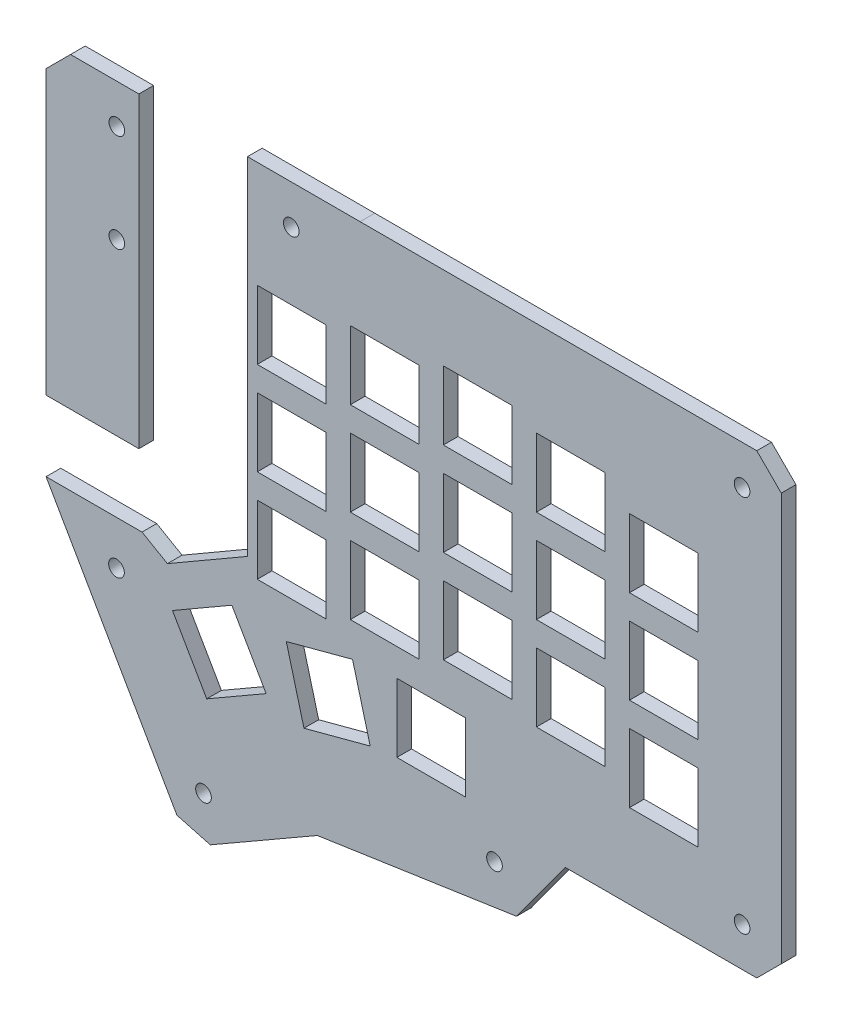
SolidWorks part; units mm, degrees
ref_plane "Plan de face" through (0, 0, 0) normal (0, 0, 1) x (1, 0, 0)
ref_plane "Plan de dessus" through (0, 0, 0) normal (0, 1, 0) x (1, 0, 0)
ref_plane "Plan de droite" through (0, 0, 0) normal (1, 0, 0) x (0, 0, -1)
sketch "Switchplate" plane through (0, 0, 0) normal (0, 0, 1) x (1, 0, 0)
  line L0 (-117.3419, -15.4198) -> (-103.3409, -15.4198)
  line L1 (-103.3409, -15.4198) -> (-103.3409, -29.4208)
  line L2 (-103.3409, -29.4208) -> (-117.3419, -29.4208)
  line L3 (-117.3419, -29.4208) -> (-117.3419, -15.4198)
  line L4 (-98.3406, -27.0457) -> (-98.3406, -13.0447)
  line L5 (-98.3406, -13.0447) -> (-84.3396, -13.0447)
  line L6 (-84.3396, -13.0447) -> (-84.3396, -27.0457)
  line L7 (-84.3396, -27.0457) -> (-98.3406, -27.0457)
  line L8 (-79.3392, -24.6705) -> (-79.3392, -10.6695)
  line L9 (-79.3392, -10.6695) -> (-65.3382, -10.6695)
  line L10 (-65.3382, -10.6695) -> (-65.3382, -24.6705)
  line L11 (-65.3382, -24.6705) -> (-79.3392, -24.6705)
  line L12 (-60.3379, -27.0457) -> (-60.3379, -13.0447)
  line L13 (-60.3379, -13.0447) -> (-46.3369, -13.0447)
  line L14 (-46.3369, -13.0447) -> (-46.3369, -27.0457)
  line L15 (-46.3369, -27.0457) -> (-60.3379, -27.0457)
  line L16 (-41.3365, -31.796) -> (-41.3365, -17.795)
  line L17 (-41.3365, -17.795) -> (-27.3355, -17.795)
  line L18 (-27.3355, -17.795) -> (-27.3355, -31.796)
  line L19 (-27.3355, -31.796) -> (-41.3365, -31.796)
  line L24 (-117.3419, -34.4212) -> (-103.3409, -34.4212)
  line L25 (-103.3409, -34.4212) -> (-103.3409, -48.4222)
  line L26 (-103.3409, -48.4222) -> (-117.3419, -48.4222)
  line L27 (-117.3419, -48.4222) -> (-117.3419, -34.4212)
  line L28 (-98.3406, -32.046) -> (-84.3396, -32.046)
  line L29 (-84.3396, -32.046) -> (-84.3396, -46.047)
  line L30 (-84.3396, -46.047) -> (-98.3406, -46.047)
  line L31 (-98.3406, -46.047) -> (-98.3406, -32.046)
  line L32 (-79.3392, -29.6709) -> (-65.3382, -29.6709)
  line L33 (-65.3382, -29.6709) -> (-65.3382, -43.6718)
  line L34 (-65.3382, -43.6718) -> (-79.3392, -43.6718)
  line L35 (-79.3392, -43.6718) -> (-79.3392, -29.6709)
  line L36 (-60.3379, -32.046) -> (-46.3369, -32.046)
  line L37 (-46.3369, -32.046) -> (-46.3369, -46.047)
  line L38 (-46.3369, -46.047) -> (-60.3379, -46.047)
  line L39 (-60.3379, -46.047) -> (-60.3379, -32.046)
  line L40 (-41.3365, -36.7964) -> (-27.3355, -36.7964)
  line L41 (-27.3355, -36.7964) -> (-27.3355, -50.7973)
  line L42 (-27.3355, -50.7973) -> (-41.3365, -50.7973)
  line L43 (-41.3365, -50.7973) -> (-41.3365, -36.7964)
  line L52 (-41.3365, -55.7977) -> (-27.3355, -55.7977)
  line L53 (-27.3355, -55.7977) -> (-27.3355, -69.7987)
  line L54 (-27.3355, -69.7987) -> (-41.3365, -69.7987)
  line L55 (-41.3365, -69.7987) -> (-41.3365, -55.7977)
  line L56 (-60.3379, -51.0474) -> (-46.3369, -51.0474)
  line L57 (-46.3369, -51.0474) -> (-46.3369, -65.0484)
  line L58 (-46.3369, -65.0484) -> (-60.3379, -65.0484)
  line L59 (-60.3379, -65.0484) -> (-60.3379, -51.0474)
  line L60 (-79.3392, -48.6722) -> (-65.3382, -48.6722)
  line L61 (-65.3382, -48.6722) -> (-65.3382, -62.6732)
  line L62 (-65.3382, -62.6732) -> (-79.3392, -62.6732)
  line L63 (-79.3392, -62.6732) -> (-79.3392, -48.6722)
  line L64 (-98.3406, -51.0474) -> (-84.3396, -51.0474)
  line L65 (-84.3396, -51.0474) -> (-84.3396, -65.0484)
  line L66 (-84.3396, -65.0484) -> (-98.3406, -65.0484)
  line L67 (-98.3406, -65.0484) -> (-98.3406, -51.0474)
  line L68 (-117.3419, -53.4225) -> (-103.3409, -53.4225)
  line L69 (-103.3409, -53.4225) -> (-103.3409, -67.4235)
  line L70 (-103.3409, -67.4235) -> (-117.3419, -67.4235)
  line L71 (-117.3419, -67.4235) -> (-117.3419, -53.4225)
  line L72 (-88.8399, -70.6738) -> (-74.8389, -70.6738)
  line L73 (-74.8389, -70.6738) -> (-74.8389, -84.6747)
  line L74 (-74.8389, -84.6747) -> (-88.8399, -84.6747)
  line L75 (-88.8399, -84.6747) -> (-88.8399, -70.6738)
  line L76 (-111.4175, -75.4665) -> (-97.8899, -71.8565)
  line L77 (-97.8899, -71.8565) -> (-94.28, -85.3841)
  line L78 (-94.28, -85.3841) -> (-107.8075, -88.9941)
  line L79 (-107.8075, -88.9941) -> (-111.4175, -75.4665)
  line L80 (-134.6581, -81.5997) -> (-122.5281, -74.6075)
  line L81 (-122.5281, -74.6075) -> (-115.5359, -86.7375)
  line L82 (-115.5359, -86.7375) -> (-127.6659, -93.7297)
  line L83 (-127.6659, -93.7297) -> (-134.6581, -81.5997)
  line L86 (-6.3391, -71.9336) -> (-62.0853, -71.9336) construction
  line L89 (-72.824, -86.6446) -> (-62.0853, -71.9336) construction
  line L96 (-109.7697, -91.4639) -> (-73.0906, -86.6918) construction
  line L97 (-124.664, -99.8297) -> (-110.3971, -91.5881) construction
  line L98 (-139.9408, -76.5013) -> (-126.7151, -99.4281) construction
  line L99 (-119.8527, -15.5421) -> (-139.6028, -15.5421) construction
  line L100 (-100.8528, -13.2921) -> (-118.8527, -13.2921) construction
  line L101 (-63.8455, -8.5421) -> (-80.8528, -8.5421) construction
  line L102 (-44.8455, -10.792) -> (-62.8485, -10.792) construction
  line L103 (-25.8456, -15.5421) -> (-43.8486, -15.5421) construction
  line L104 (-6.8456, -15.5421) -> (-23.8529, -15.5421) construction
  line L105 (-6.2741, -71.3672) -> (-6.2741, -16.1136) construction
  line L106 (-23.8529, -71.9423) -> (-6.8456, -71.9423) construction
  line L107 (-61.8455, -71.9423) -> (-25.8456, -71.9423) construction
  line L108 (-72.6738, -86.4911) -> (-62.1363, -72.0583) construction
  line L109 (-140.1743, -16.1136) -> (-140.1743, -75.5958) construction
  line L110 (-134.3462, 1.5705) -> (-134.3466, -55.7217) construction
  line L111 (-134.3466, -55.7217) -> (-160.479, -70.8411) construction
  line L112 (-160.479, -70.8411) -> (-133.7613, -117.344)
  line L113 (-126.937, -119.1852) -> (-105.0783, -106.604)
  line L114 (-105.0783, -106.604) -> (-64.4097, -100.5586)
  line L115 (-64.4097, -100.5586) -> (-54.4636, -86.9336)
  line L116 (-15.3391, -86.9336) -> (-54.4636, -86.9336)
  line L117 (-10.3391, -81.9336) -> (-10.3391, 1.3161)
  line L122 (-15.3391, 6.3163) -> (-96.3444, 6.3209)
  line L129 (8.6609, -86.9336) -> (8.6609, -0.6796) construction
  line L130 (-48.3431, 6.3182) -> (-96.3444, 6.3209) construction
  line L131 (-115.3458, 1.5705) -> (-134.3462, 1.5705) construction
  line L132 (-160.479, -3.4295) -> (-160.479, -70.8411)
  line L134 (-119.3463, 1.5705) -> (-119.3466, -64.3728)
  line L135 (-119.3466, -64.3728) -> (-135.695, -73.8315)
  line L136 (-140.0228, -71.3355) -> (-140.0228, 1.5705) construction
  line L138 (-160.479, -70.8411) -> (-131.2704, -121.6794) construction
  line L139 (-131.2704, -121.6794) -> (-105.0783, -106.604) construction
  line L140 (-133.7613, -117.344) -> (-126.937, -119.1852)
  line L142 (-10.3391, 1.3161) -> (-15.3391, 6.3163)
  line L143 (8.6609, -86.9336) -> (-54.4636, -86.9336) construction
  line L147 (-103.3409, 6.3209) -> (-96.3444, 6.3209)
  line L148 (-103.3409, 6.3209) -> (-119.3463, 6.3209)
  line L149 (-119.3463, 6.3209) -> (-119.3463, 1.5705)
  line L150 (-140.0228, 1.5705) -> (-140.0228, 6.3209) construction
  line L151 (-141.5228, 6.3209) -> (-155.479, 6.3209)
  line L152 (-160.479, 1.3209) -> (-160.479, -3.4295)
  line L153 (-155.479, 6.3209) -> (-160.479, 1.3209)
  line L154 (8.6609, -1.685) -> (-119.3463, -1.6779) construction
  line L155 (-146.0924, -79.8227) -> (-128.3223, -110.752) construction
  line L156 (-128.3223, -110.752) -> (-107.7547, -98.9139) construction
  line L157 (-140.8899, -76.8336) -> (-126.1111, -102.5565) construction
  line L158 (-126.1111, -102.5565) -> (-109.762, -93.1464) construction
  line L159 (-109.762, -93.1464) -> (-72.2631, -87.5722) construction
  line L160 (-72.2631, -87.5722) -> (-61.5772, -72.9336) construction
  line L161 (-5.3391, -72.9336) -> (-61.5772, -72.9336) construction
  line L162 (-5.3391, -72.9336) -> (-5.3391, -14.6796) construction
  line L163 (-5.3391, -14.6796) -> (-43.3418, -14.6796) construction
  line L164 (-43.3418, -14.6796) -> (-43.3418, -9.9293) construction
  line L165 (-43.3418, -9.9293) -> (-62.3431, -9.9293) construction
  line L166 (-62.3431, -9.9293) -> (-62.3431, -7.681) construction
  line L167 (-62.3431, -7.681) -> (-82.3444, -7.6799) construction
  line L168 (-82.3444, -7.6799) -> (-82.3444, -9.9293) construction
  line L169 (-82.3444, -9.9293) -> (-101.3458, -9.9293) construction
  line L170 (-101.3458, -9.9293) -> (-101.3458, -12.4295) construction
  line L171 (-101.3458, -12.4295) -> (-120.3463, -12.4295) construction
  line L172 (-120.3463, -12.4295) -> (-120.3466, -64.3728) construction
  line L173 (-119.8474, -63.5072) -> (-140.5236, -75.4699) construction
  line L174 (-107.7547, -98.9139) -> (-68.8973, -93.1378) construction
  line L175 (-68.8973, -93.1378) -> (-58.5285, -78.9336) construction
  line L176 (0.6609, -78.9336) -> (-58.5285, -78.9336) construction
  line L177 (-18.3391, -78.9336) -> (-18.3391, -1.6845) construction
  line L178 (-62.3428, -1.681) -> (-82.3441, -1.6799) construction
  line L179 (0.6609, -78.9336) -> (0.6609, -14.6796) construction
  line L180 (-146.0228, -76.3355) -> (-146.0228, 1.5705) construction
  line L181 (-140.0228, -76.3355) -> (-140.0228, 1.5705) construction
  line L182 (-135.695, -73.8315) -> (-141.5228, -70.4704)
  line L185 (-10.3391, -81.9336) -> (-15.3391, -86.9336)
  line L186 (-146.0228, -1.6779) -> (-146.0228, -19.3841) construction
  line L187 (-146.0228, -1.6779) -> (-146.0228, -21.6824) construction
  line L188 (-141.5228, -70.4704) -> (-141.5228, 1.5705)
  line L189 (-141.5228, 1.5705) -> (-141.5228, 6.3209)
  line L191 (-141.5228, -71.3355) -> (-141.5228, 1.5705) construction
  line L217 (-6.3391, -71.9336) -> (-6.3391, -15.6796) construction
  line L220 (-6.3391, -15.6796) -> (-44.3418, -15.6796) construction
  line L221 (-44.3418, -15.6796) -> (-44.3418, -10.9293) construction
  line L222 (-44.3418, -10.9293) -> (-63.3431, -10.9293) construction
  line L223 (-63.3431, -10.9293) -> (-63.3431, -8.681) construction
  line L224 (-63.3431, -8.681) -> (-81.3444, -8.68) construction
  line L225 (-81.3444, -8.68) -> (-81.3444, -10.9293) construction
  line L226 (-81.3444, -10.9293) -> (-100.3458, -10.9293) construction
  line L227 (-100.3458, -10.9293) -> (-100.3458, -13.4295) construction
  line L228 (-100.3458, -13.4295) -> (-119.3463, -13.4295) construction
  line L231 (-119.3463, -13.4295) -> (-119.3466, -64.3728) construction
  line L232 (-119.3466, -64.3728) -> (-140.0228, -76.3355) construction
  line L233 (-140.0228, -76.3355) -> (-125.7426, -101.1906) construction
  line L234 (-125.7426, -101.1906) -> (-110.0965, -92.1851) construction
  line L235 (-110.0965, -92.1851) -> (-72.824, -86.6446) construction
  line L328 (-48.3431, 4.0707) -> (-48.3431, 6.3182) construction
  line L329 (-29.3418, 4.0707) -> (-48.3431, 4.0707) construction
  line L330 (-29.3418, -0.6796) -> (-29.3418, 4.0707) construction
  line L331 (8.6609, -0.6796) -> (-29.3418, -0.6796) construction
  line L332 (-115.3458, 4.0707) -> (-115.3458, 1.5705) construction
  line L333 (-96.3444, 4.0707) -> (-115.3458, 4.0707) construction
  line L334 (-96.3444, 6.3209) -> (-96.3444, 4.0707) construction
  circle A2 centre (-18.3391, -1.6845) radius 1.6
  circle A3 centre (-18.3391, -1.6845) radius 3 construction
  circle A4 centre (-110.3971, -1.6784) radius 1.6
  circle A5 centre (-18.3391, -78.9336) radius 1.6
  circle A6 centre (-68.8973, -93.1378) radius 1.6
  circle A7 centre (-128.3223, -110.752) radius 1.6
  circle A8 centre (-146.0924, -79.8227) radius 1.6
  circle A9 centre (-146.0228, -1.6779) radius 1.6
  circle A10 centre (-146.0228, -21.6824) radius 1.6
  point P138 (-160.479, 1.5705)
  point P139 (-10.3391, 6.3161)
  point P150 (-160.479, 6.3209)
  point P200 (-10.3391, -86.9336)
  dimension "D3" = 3.2
  dimension "D4" = 6
  dimension "D6" = 3.2
  dimension "D7" = 3.2
  dimension "D8" = 3.2
  dimension "D9" = 3.2
  dimension "D10" = 3.2
  dimension "D15" = 3.2
  dimension "D16" = 3.2
  dimension "D2" = 6
  dimension "D1" = 15
  dimension "D5" = 1
  dimension "D13" = 6
  dimension "D17" = 1.5
extrude "Boss.-Extru.2" add sketch "Switchplate" along normal blind 3
sketch "Esquisse1" plane through (0, 0, 3) normal (0, 0, 1) x (1, 0, 0)
  line L0 (-160.479, -70.8411) -> (-140.0228, -70.8411)
  line L1 (-140.0228, -71.3355) -> (-140.0228, 1.5705) construction
  line L2 (-117.3419, -53.4225) -> (-140.0228, -53.4225) construction
  line L3 (-140.0228, -53.4225) -> (-140.0228, -56.4207) construction
  line L4 (-140.0228, -56.4207) -> (-140.0228, -70.8411)
  line L5 (-140.0228, -56.4207) -> (-160.479, -56.4207)
  line L6 (-160.479, -3.4295) -> (-160.479, -70.8411) construction
  line L7 (-160.479, -56.4207) -> (-160.479, -70.8411)
extrude "Enlèv. mat.-Extru.1" cut sketch "Esquisse1" against normal blind 10
sketch "Esquisse2" plane through (0, 0, 3) normal (0, 0, 1) x (1, 0, 0)
  line L0 (-81.3444, -8.68) -> (-81.3444, -10.9293) construction
  line L1 (-63.3431, -8.681) -> (-81.3444, -8.68) construction
  line L2 (-63.3431, -10.9293) -> (-63.3431, -8.681) construction
  line L3 (-44.3418, -10.9293) -> (-63.3431, -10.9293) construction
  line L4 (-44.3418, -15.6796) -> (-44.3418, -10.9293) construction
  line L5 (-6.3391, -15.6796) -> (-44.3418, -15.6796) construction
  line L6 (-6.3391, -71.9336) -> (-6.3391, -15.6796) construction
  line L7 (-6.3391, -71.9336) -> (-62.0853, -71.9336) construction
  line L8 (-72.824, -86.6446) -> (-62.0853, -71.9336) construction
  line L9 (-110.0965, -92.1851) -> (-72.824, -86.6446) construction
  line L10 (-125.7426, -101.1906) -> (-110.0965, -92.1851) construction
  line L11 (-140.0228, -76.3355) -> (-125.7426, -101.1906) construction
  line L12 (-119.3466, -64.3728) -> (-140.0228, -76.3355) construction
  line L13 (-119.3463, -13.4295) -> (-119.3466, -64.3728) construction
  line L14 (-100.3458, -13.4295) -> (-119.3463, -13.4295) construction
  line L15 (-100.3458, -10.9293) -> (-100.3458, -13.4295) construction
  line L16 (-81.3444, -10.9293) -> (-100.3458, -10.9293) construction
  line L17 (-81.3444, -8.68) -> (-81.3444, -10.9293)
  line L18 (-63.3431, -8.681) -> (-81.3444, -8.68)
  line L19 (-63.3431, -10.9293) -> (-63.3431, -8.681)
  line L20 (-44.3418, -10.9293) -> (-63.3431, -10.9293)
  line L21 (-44.3418, -15.6796) -> (-44.3418, -10.9293)
  line L22 (-6.3391, -15.6796) -> (-44.3418, -15.6796)
  line L23 (-6.3391, -71.9336) -> (-6.3391, -15.6796)
  line L24 (-6.3391, -71.9336) -> (-62.0853, -71.9336)
  line L25 (-72.824, -86.6446) -> (-62.0853, -71.9336)
  line L26 (-110.0965, -92.1851) -> (-72.824, -86.6446)
  line L27 (-125.7426, -101.1906) -> (-110.0965, -92.1851)
  line L28 (-140.0228, -76.3355) -> (-125.7426, -101.1906)
  line L29 (-119.3466, -64.3728) -> (-140.0228, -76.3355)
  line L30 (-119.3463, -13.4295) -> (-119.3466, -64.3728)
  line L31 (-100.3458, -13.4295) -> (-119.3463, -13.4295)
  line L32 (-100.3458, -10.9293) -> (-100.3458, -13.4295)
  line L33 (-81.3444, -10.9293) -> (-100.3458, -10.9293)
  line L34 (-127.6659, -93.7297) -> (-134.6581, -81.5997) construction
  line L35 (-115.5359, -86.7375) -> (-127.6659, -93.7297) construction
  line L36 (-122.5281, -74.6075) -> (-115.5359, -86.7375) construction
  line L37 (-134.6581, -81.5997) -> (-122.5281, -74.6075) construction
  line L38 (-107.8075, -88.9941) -> (-111.4175, -75.4665) construction
  line L39 (-94.28, -85.3841) -> (-107.8075, -88.9941) construction
  line L40 (-97.8899, -71.8565) -> (-94.28, -85.3841) construction
  line L41 (-111.4175, -75.4665) -> (-97.8899, -71.8565) construction
  line L42 (-88.8399, -84.6747) -> (-88.8399, -70.6738) construction
  line L43 (-74.8389, -84.6747) -> (-88.8399, -84.6747) construction
  line L44 (-74.8389, -70.6738) -> (-74.8389, -84.6747) construction
  line L45 (-88.8399, -70.6738) -> (-74.8389, -70.6738) construction
  line L46 (-98.3406, -65.0484) -> (-98.3406, -51.0474) construction
  line L47 (-84.3396, -65.0484) -> (-98.3406, -65.0484) construction
  line L48 (-84.3396, -51.0474) -> (-84.3396, -65.0484) construction
  line L49 (-98.3406, -51.0474) -> (-84.3396, -51.0474) construction
  line L50 (-117.3419, -67.4235) -> (-117.3419, -53.4225) construction
  line L51 (-103.3409, -67.4235) -> (-117.3419, -67.4235) construction
  line L52 (-103.3409, -53.4225) -> (-103.3409, -67.4235) construction
  line L53 (-117.3419, -53.4225) -> (-103.3409, -53.4225) construction
  line L54 (-117.3419, -48.4222) -> (-117.3419, -34.4212) construction
  line L55 (-103.3409, -48.4222) -> (-117.3419, -48.4222) construction
  line L56 (-103.3409, -34.4212) -> (-103.3409, -48.4222) construction
  line L57 (-117.3419, -34.4212) -> (-103.3409, -34.4212) construction
  line L58 (-98.3406, -46.047) -> (-98.3406, -32.046) construction
  line L59 (-84.3396, -46.047) -> (-98.3406, -46.047) construction
  line L60 (-84.3396, -32.046) -> (-84.3396, -46.047) construction
  line L61 (-98.3406, -32.046) -> (-84.3396, -32.046) construction
  line L62 (-79.3392, -43.6718) -> (-79.3392, -29.6709) construction
  line L63 (-65.3382, -43.6718) -> (-79.3392, -43.6718) construction
  line L64 (-65.3382, -29.6709) -> (-65.3382, -43.6718) construction
  line L65 (-79.3392, -29.6709) -> (-65.3382, -29.6709) construction
  line L66 (-60.3379, -46.047) -> (-60.3379, -32.046) construction
  line L67 (-46.3369, -46.047) -> (-60.3379, -46.047) construction
  line L68 (-46.3369, -32.046) -> (-46.3369, -46.047) construction
  line L69 (-60.3379, -32.046) -> (-46.3369, -32.046) construction
  line L70 (-79.3392, -62.6732) -> (-79.3392, -48.6722) construction
  line L71 (-65.3382, -62.6732) -> (-79.3392, -62.6732) construction
  line L72 (-65.3382, -48.6722) -> (-65.3382, -62.6732) construction
  line L73 (-79.3392, -48.6722) -> (-65.3382, -48.6722) construction
  line L74 (-60.3379, -65.0484) -> (-60.3379, -51.0474) construction
  line L75 (-46.3369, -65.0484) -> (-60.3379, -65.0484) construction
  line L76 (-46.3369, -51.0474) -> (-46.3369, -65.0484) construction
  line L77 (-60.3379, -51.0474) -> (-46.3369, -51.0474) construction
  line L78 (-41.3365, -69.7987) -> (-41.3365, -55.7977) construction
  line L79 (-27.3355, -69.7987) -> (-41.3365, -69.7987) construction
  line L80 (-27.3355, -55.7977) -> (-27.3355, -69.7987) construction
  line L81 (-41.3365, -55.7977) -> (-27.3355, -55.7977) construction
  line L82 (-22.3347, -69.7987) -> (-22.3347, -55.7977) construction
  line L83 (-8.3337, -69.7987) -> (-22.3347, -69.7987) construction
  line L84 (-8.3337, -55.7977) -> (-8.3337, -69.7987) construction
  line L85 (-22.3347, -55.7977) -> (-8.3337, -55.7977) construction
  line L86 (-41.3365, -50.7973) -> (-41.3365, -36.7964) construction
  line L87 (-27.3355, -50.7973) -> (-41.3365, -50.7973) construction
  line L88 (-27.3355, -36.7964) -> (-27.3355, -50.7973) construction
  line L89 (-41.3365, -36.7964) -> (-27.3355, -36.7964) construction
  line L90 (-22.3347, -50.7973) -> (-22.3347, -36.7964) construction
  line L91 (-8.3337, -50.7973) -> (-22.3347, -50.7973) construction
  line L92 (-8.3337, -36.7964) -> (-8.3337, -50.7973) construction
  line L93 (-22.3347, -36.7964) -> (-8.3337, -36.7964) construction
  line L94 (-22.3347, -31.796) -> (-22.3347, -17.795) construction
  line L95 (-8.3337, -31.796) -> (-22.3347, -31.796) construction
  line L96 (-8.3337, -17.795) -> (-8.3337, -31.796) construction
  line L97 (-22.3347, -17.795) -> (-8.3337, -17.795) construction
  line L98 (-41.3365, -31.796) -> (-41.3365, -17.795) construction
  line L99 (-27.3355, -31.796) -> (-41.3365, -31.796) construction
  line L100 (-27.3355, -17.795) -> (-27.3355, -31.796) construction
  line L101 (-41.3365, -17.795) -> (-27.3355, -17.795) construction
  line L102 (-60.3379, -27.0457) -> (-60.3379, -13.0447) construction
  line L103 (-46.3369, -27.0457) -> (-60.3379, -27.0457) construction
  line L104 (-46.3369, -13.0447) -> (-46.3369, -27.0457) construction
  line L105 (-60.3379, -13.0447) -> (-46.3369, -13.0447) construction
  line L106 (-79.3392, -24.6705) -> (-79.3392, -10.6695) construction
  line L107 (-65.3382, -24.6705) -> (-79.3392, -24.6705) construction
  line L108 (-65.3382, -10.6695) -> (-65.3382, -24.6705) construction
  line L109 (-79.3392, -10.6695) -> (-65.3382, -10.6695) construction
  line L110 (-98.3406, -27.0457) -> (-98.3406, -13.0447) construction
  line L111 (-84.3396, -27.0457) -> (-98.3406, -27.0457) construction
  line L112 (-84.3396, -13.0447) -> (-84.3396, -27.0457) construction
  line L113 (-98.3406, -13.0447) -> (-84.3396, -13.0447) construction
  line L114 (-117.3419, -29.4208) -> (-117.3419, -15.4198) construction
  line L115 (-103.3409, -29.4208) -> (-117.3419, -29.4208) construction
  line L116 (-103.3409, -15.4198) -> (-103.3409, -29.4208) construction
  line L117 (-117.3419, -15.4198) -> (-103.3409, -15.4198) construction
  line L118 (-127.6659, -93.7297) -> (-134.6581, -81.5997)
  line L119 (-115.5359, -86.7375) -> (-127.6659, -93.7297)
  line L120 (-122.5281, -74.6075) -> (-115.5359, -86.7375)
  line L121 (-134.6581, -81.5997) -> (-122.5281, -74.6075)
  line L122 (-107.8075, -88.9941) -> (-111.4175, -75.4665)
  line L123 (-94.28, -85.3841) -> (-107.8075, -88.9941)
  line L124 (-97.8899, -71.8565) -> (-94.28, -85.3841)
  line L125 (-111.4175, -75.4665) -> (-97.8899, -71.8565)
  line L126 (-88.8399, -84.6747) -> (-88.8399, -70.6738)
  line L127 (-74.8389, -84.6747) -> (-88.8399, -84.6747)
  line L128 (-74.8389, -70.6738) -> (-74.8389, -84.6747)
  line L129 (-88.8399, -70.6738) -> (-74.8389, -70.6738)
  line L130 (-98.3406, -65.0484) -> (-98.3406, -51.0474)
  line L131 (-84.3396, -65.0484) -> (-98.3406, -65.0484)
  line L132 (-84.3396, -51.0474) -> (-84.3396, -65.0484)
  line L133 (-98.3406, -51.0474) -> (-84.3396, -51.0474)
  line L134 (-117.3419, -67.4235) -> (-117.3419, -53.4225)
  line L135 (-103.3409, -67.4235) -> (-117.3419, -67.4235)
  line L136 (-103.3409, -53.4225) -> (-103.3409, -67.4235)
  line L137 (-117.3419, -53.4225) -> (-103.3409, -53.4225)
  line L138 (-117.3419, -48.4222) -> (-117.3419, -34.4212)
  line L139 (-103.3409, -48.4222) -> (-117.3419, -48.4222)
  line L140 (-103.3409, -34.4212) -> (-103.3409, -48.4222)
  line L141 (-117.3419, -34.4212) -> (-103.3409, -34.4212)
  line L142 (-98.3406, -46.047) -> (-98.3406, -32.046)
  line L143 (-84.3396, -46.047) -> (-98.3406, -46.047)
  line L144 (-84.3396, -32.046) -> (-84.3396, -46.047)
  line L145 (-98.3406, -32.046) -> (-84.3396, -32.046)
  line L146 (-79.3392, -43.6718) -> (-79.3392, -29.6709)
  line L147 (-65.3382, -43.6718) -> (-79.3392, -43.6718)
  line L148 (-65.3382, -29.6709) -> (-65.3382, -43.6718)
  line L149 (-79.3392, -29.6709) -> (-65.3382, -29.6709)
  line L150 (-60.3379, -46.047) -> (-60.3379, -32.046)
  line L151 (-46.3369, -46.047) -> (-60.3379, -46.047)
  line L152 (-46.3369, -32.046) -> (-46.3369, -46.047)
  line L153 (-60.3379, -32.046) -> (-46.3369, -32.046)
  line L154 (-79.3392, -62.6732) -> (-79.3392, -48.6722)
  line L155 (-65.3382, -62.6732) -> (-79.3392, -62.6732)
  line L156 (-65.3382, -48.6722) -> (-65.3382, -62.6732)
  line L157 (-79.3392, -48.6722) -> (-65.3382, -48.6722)
  line L158 (-60.3379, -65.0484) -> (-60.3379, -51.0474)
  line L159 (-46.3369, -65.0484) -> (-60.3379, -65.0484)
  line L160 (-46.3369, -51.0474) -> (-46.3369, -65.0484)
  line L161 (-60.3379, -51.0474) -> (-46.3369, -51.0474)
  line L162 (-41.3365, -69.7987) -> (-41.3365, -55.7977)
  line L163 (-27.3355, -69.7987) -> (-41.3365, -69.7987)
  line L164 (-27.3355, -55.7977) -> (-27.3355, -69.7987)
  line L165 (-41.3365, -55.7977) -> (-27.3355, -55.7977)
  line L166 (-22.3347, -69.7987) -> (-22.3347, -55.7977)
  line L167 (-8.3337, -69.7987) -> (-22.3347, -69.7987)
  line L168 (-8.3337, -55.7977) -> (-8.3337, -69.7987)
  line L169 (-22.3347, -55.7977) -> (-8.3337, -55.7977)
  line L170 (-41.3365, -50.7973) -> (-41.3365, -36.7964)
  line L171 (-27.3355, -50.7973) -> (-41.3365, -50.7973)
  line L172 (-27.3355, -36.7964) -> (-27.3355, -50.7973)
  line L173 (-41.3365, -36.7964) -> (-27.3355, -36.7964)
  line L174 (-22.3347, -50.7973) -> (-22.3347, -36.7964)
  line L175 (-8.3337, -50.7973) -> (-22.3347, -50.7973)
  line L176 (-8.3337, -36.7964) -> (-8.3337, -50.7973)
  line L177 (-22.3347, -36.7964) -> (-8.3337, -36.7964)
  line L178 (-22.3347, -31.796) -> (-22.3347, -17.795)
  line L179 (-8.3337, -31.796) -> (-22.3347, -31.796)
  line L180 (-8.3337, -17.795) -> (-8.3337, -31.796)
  line L181 (-22.3347, -17.795) -> (-8.3337, -17.795)
  line L182 (-41.3365, -31.796) -> (-41.3365, -17.795)
  line L183 (-27.3355, -31.796) -> (-41.3365, -31.796)
  line L184 (-27.3355, -17.795) -> (-27.3355, -31.796)
  line L185 (-41.3365, -17.795) -> (-27.3355, -17.795)
  line L186 (-60.3379, -27.0457) -> (-60.3379, -13.0447)
  line L187 (-46.3369, -27.0457) -> (-60.3379, -27.0457)
  line L188 (-46.3369, -13.0447) -> (-46.3369, -27.0457)
  line L189 (-60.3379, -13.0447) -> (-46.3369, -13.0447)
  line L190 (-79.3392, -24.6705) -> (-79.3392, -10.6695)
  line L191 (-65.3382, -24.6705) -> (-79.3392, -24.6705)
  line L192 (-65.3382, -10.6695) -> (-65.3382, -24.6705)
  line L193 (-79.3392, -10.6695) -> (-65.3382, -10.6695)
  line L194 (-98.3406, -27.0457) -> (-98.3406, -13.0447)
  line L195 (-84.3396, -27.0457) -> (-98.3406, -27.0457)
  line L196 (-84.3396, -13.0447) -> (-84.3396, -27.0457)
  line L197 (-98.3406, -13.0447) -> (-84.3396, -13.0447)
  line L198 (-117.3419, -29.4208) -> (-117.3419, -15.4198)
  line L199 (-103.3409, -29.4208) -> (-117.3419, -29.4208)
  line L200 (-103.3409, -15.4198) -> (-103.3409, -29.4208)
  line L201 (-117.3419, -15.4198) -> (-103.3409, -15.4198)
